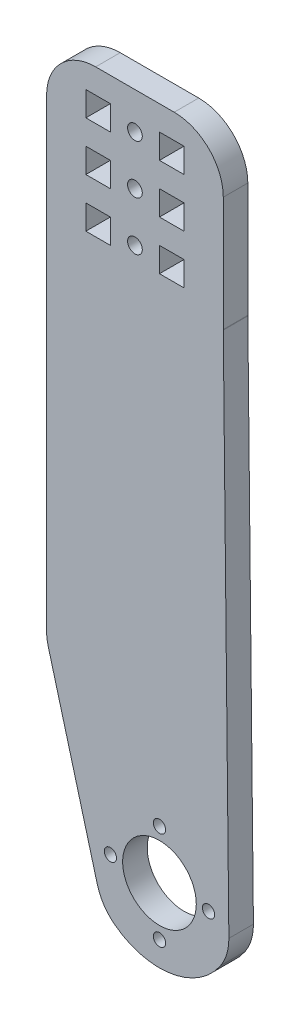
SolidWorks part; units mm, degrees
ref_plane "Front Plane" through (0, 0, 0) normal (0, 0, 1) x (1, 0, 0)
ref_plane "Top Plane" through (0, 0, 0) normal (0, 1, 0) x (1, 0, 0)
ref_plane "Right Plane" through (0, 0, 0) normal (1, 0, 0) x (0, 0, -1)
sketch "Sketch1" plane through (0, 0, 0) normal (0, 0, 1) x (1, 0, 0)
  line L0 (0, 44.1386) -> (10.9849, 3.5202)
  line L5 (36, 116.6039) -> (37.1646, 7.5639)
  line L6 (0, 150) -> (0, 44.1386)
  line L7 (18, 102) -> (18, 84.2884) construction
  line L11 (18, 102) -> (18, 149.1304) construction
  line L13 (0, 0) -> (0, 44.1386) construction
  line L14 (18, 142.5) -> (18, 122.5) construction
  line L17 (0, 150) -> (36, 150)
  line L21 (36, 150) -> (36, 116.6039)
  arc A13 (10.9849, 3.5202) -> (37.1646, 7.5639) centre (23, 12.5) ccw
  point P30 (18, 132.5)
  line B0 (23, 22.5) -> (23, 2.5) construction
  line B1 (23, 12.5) -> (30.0711, 19.5711) construction
  circle B2 centre (23, 12.5) radius 7.5
  circle B3 centre (23, 22.5) radius 1.25
  circle B4 centre (13, 12.5) radius 1.25
  circle B5 centre (23, 2.5) radius 1.25
  circle B6 centre (33, 12.5) radius 1.25
  line B7 (13, 142.5) -> (23, 142.5) construction
  line B8 (13, 145) -> (8, 145)
  line B9 (13, 145) -> (13, 140)
  line B10 (13, 140) -> (8, 140)
  line B11 (8, 145) -> (8, 140)
  line B12 (23, 145) -> (28, 145)
  line B13 (23, 145) -> (23, 140)
  line B14 (23, 140) -> (28, 140)
  line B15 (28, 145) -> (28, 140)
  line B16 (18, 142.5) -> (18, 149.4724) construction
  circle B17 centre (18, 142.5) radius 1.5
  line B18 (13, 122.5) -> (23, 122.5) construction
  line B19 (13, 125) -> (8, 125)
  line B20 (13, 125) -> (13, 120)
  line B21 (13, 120) -> (8, 120)
  line B22 (8, 125) -> (8, 120)
  line B23 (23, 125) -> (28, 125)
  line B24 (23, 125) -> (23, 120)
  line B25 (23, 120) -> (28, 120)
  line B26 (28, 125) -> (28, 120)
  line B27 (18, 122.5) -> (18, 129.4724) construction
  circle B28 centre (18, 122.5) radius 1.5
  line B29 (13, 132.5) -> (23, 132.5) construction
  line B30 (13, 135) -> (8, 135)
  line B31 (13, 135) -> (13, 130)
  line B32 (13, 130) -> (8, 130)
  line B33 (8, 135) -> (8, 130)
  line B34 (23, 135) -> (28, 135)
  line B35 (23, 135) -> (23, 130)
  line B36 (23, 130) -> (28, 130)
  line B37 (28, 135) -> (28, 130)
  circle B38 centre (18, 132.5) radius 1.5
  dimension "D6" = 10
  dimension "D7" = 150
  dimension "D3" = 15
  dimension "D4" = 5
  dimension "D2" = 12.5
  dimension "D5" = 8
  dimension "D8" = 7.5
  dimension "D11" = 15
sketch_block_instance "Insert_Reducteur_GP26-1"
sketch_block "Insert_Reducteur_GP26" parameters "D1"=15, "D4"=2.5, "D5"=20, "D2"=45, "D3"=45
sketch_block_instance "Trou M3 plots 5mm-3"
sketch_block "Trou M3 plots 5mm" parameters "D2"=3, "D1"=5, "D3"=5, "D4"=10
sketch_block_instance "Trou M3 plots 5mm-4"
sketch_block_instance "Trou M3 plots 5mm-5"
extrude "Boss-Extrude1" add sketch "Sketch1" along normal blind 5
fillet "Fillet1" radius 10 2 edges at (36, 150, 2.5) (0, 150, 2.5)
fillet "Fillet2" radius 10 4 edges at (36, 116.6039, 2.5) (37.1646, 7.5639, 2.5) (10.9849, 3.5202, 2.5) (0, 44.1386, 2.5)
